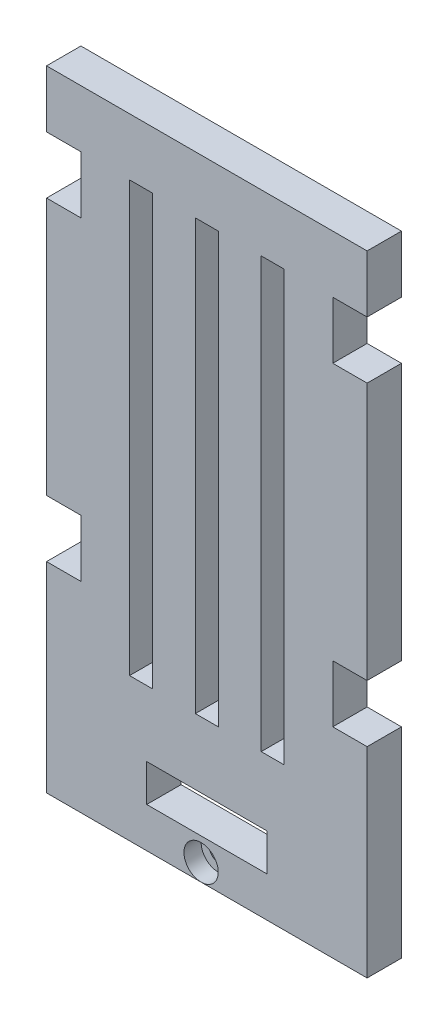
SolidWorks part; units mm, degrees
ref_plane "Plan de face" through (0, 0, 0) normal (0, 0, 1) x (1, 0, 0)
ref_plane "Plan de dessus" through (0, 0, 0) normal (0, 1, 0) x (1, 0, 0)
ref_plane "Plan de droite" through (0, 0, 0) normal (1, 0, 0) x (0, 0, -1)
sketch "Esquisse1" plane through (0, 0, 0) normal (0, 0, 1) x (1, 0, 0)
  line L1 (0, 0) -> (44, 0)
  line L2 (0, 0) -> (0, 110)
  line L3 (0, 110) -> (44, 110)
  line L4 (44, 0) -> (44, 110)
  dimension "D1" = 44
  dimension "D2" = 110
extrude "Boss.-Extru.1" add sketch "Esquisse1" along normal blind 6
sketch "Esquisse2" plane through (0, 0, 6) normal (0, 0, 1) x (1, 0, 0)
  line L0 (44, 110) -> (0, 110) construction
  line L1 (11.5, 13.5) -> (32.5, 13.5)
  line L2 (11.5, 13.5) -> (11.5, 7)
  line L3 (11.5, 7) -> (32.5, 7)
  line L4 (32.5, 13.5) -> (32.5, 7)
  line L5 (0, 110) -> (0, 0) construction
  line L6 (44, 110) -> (0, 110) construction
  line L7 (24, 100) -> (20, 100)
  line L8 (24, 100) -> (24, 25)
  line L9 (24, 25) -> (20, 25)
  line L10 (20, 100) -> (20, 25)
  line L12 (0, 110) -> (0, 0) construction
  line L13 (44, 0) -> (44, 110) construction
  line L15 (31.5, 100) -> (35.5, 100)
  line L16 (31.5, 100) -> (31.5, 25)
  line L17 (31.5, 25) -> (35.5, 25)
  line L18 (35.5, 100) -> (35.5, 25)
  line L19 (12.5, 100) -> (8.5, 100)
  line L20 (12.5, 100) -> (12.5, 25)
  line L21 (12.5, 25) -> (8.5, 25)
  line L22 (8.5, 100) -> (8.5, 25)
  dimension "D1" = 96.5
  dimension "D2" = 6.5
  dimension "D3" = 21
  dimension "D4" = 11.5
  dimension "D5" = 10
  dimension "D6" = 4
  dimension "D7" = 20
  dimension "D8" = 75
  dimension "D9" = 20
  dimension "D10" = 4
  dimension "D11" = 4
  dimension "D12" = 7.5
  dimension "D13" = 7.5
  dimension "D14" = 75
  dimension "D15" = 75
  dimension "D16" = 10
  dimension "D17" = 10
extrude "Enlèv. mat.-Extru.1" cut sketch "Esquisse2" against normal blind 6
sketch "Esquisse4" plane through (0, 0, 6) normal (0, 0, 1) x (1, 0, 0)
  line L0 (0, 110) -> (0, 0) construction
  line L1 (0, 110) -> (-6, 110)
  line L2 (0, 110) -> (0, 100)
  line L3 (0, 100) -> (-6, 100)
  line L4 (-6, 110) -> (-6, 100)
  line L5 (0, 90) -> (-6, 90)
  line L6 (0, 90) -> (0, 45)
  line L7 (0, 45) -> (-6, 45)
  line L8 (-6, 90) -> (-6, 45)
  line L9 (44, 0) -> (44, 110) construction
  line L10 (0, 0) -> (-6, 0)
  line L11 (0, 0) -> (0, 35)
  line L12 (0, 35) -> (-6, 35)
  line L13 (-6, 0) -> (-6, 35)
  line L14 (44, 0) -> (50, 0)
  line L15 (44, 0) -> (44, 35)
  line L16 (44, 35) -> (50, 35)
  line L17 (50, 0) -> (50, 35)
  line L18 (44, 45) -> (50, 45)
  line L19 (44, 45) -> (44, 90)
  line L20 (44, 90) -> (50, 90)
  line L21 (50, 45) -> (50, 90)
  line L23 (44, 110) -> (50, 110)
  line L24 (44, 110) -> (44, 100)
  line L25 (44, 100) -> (50, 100)
  line L26 (50, 110) -> (50, 100)
  dimension "D1" = 6
  dimension "D2" = 6
  dimension "D3" = 6
  dimension "D4" = 6
  dimension "D5" = 6
  dimension "D6" = 6
  dimension "D7" = 10
  dimension "D8" = 10
  dimension "D9" = 45
  dimension "D10" = 10
  dimension "D11" = 10
  dimension "D12" = 45
  dimension "D13" = 10
  dimension "D14" = 10
extrude "Boss.-Extru.2" add sketch "Esquisse4" against normal blind 6
sketch "Esquisse6" plane through (0, 0, 6) normal (0, 0, 1) x (1, 0, 0)
  line L0 (-6, 0) -> (50, 0) construction
  line L2 (-6, 35) -> (-6, 0) construction
  circle A0 centre (21, 3) radius 1.5
  dimension "D1" = 3
  dimension "D4" = 3
  dimension "D6" = 27
extrude "Enlèv. mat.-Extru.3" cut sketch "Esquisse6" against normal blind 6
sketch "Esquisse8" plane through (0, 0, 6) normal (0, 0, 1) x (1, 0, 0)
  circle A0 centre (21, 3) radius 2.995
  dimension "D1" = 5.99
extrude "Enlèv. mat.-Extru.4" cut sketch "Esquisse8" against normal blind 3
